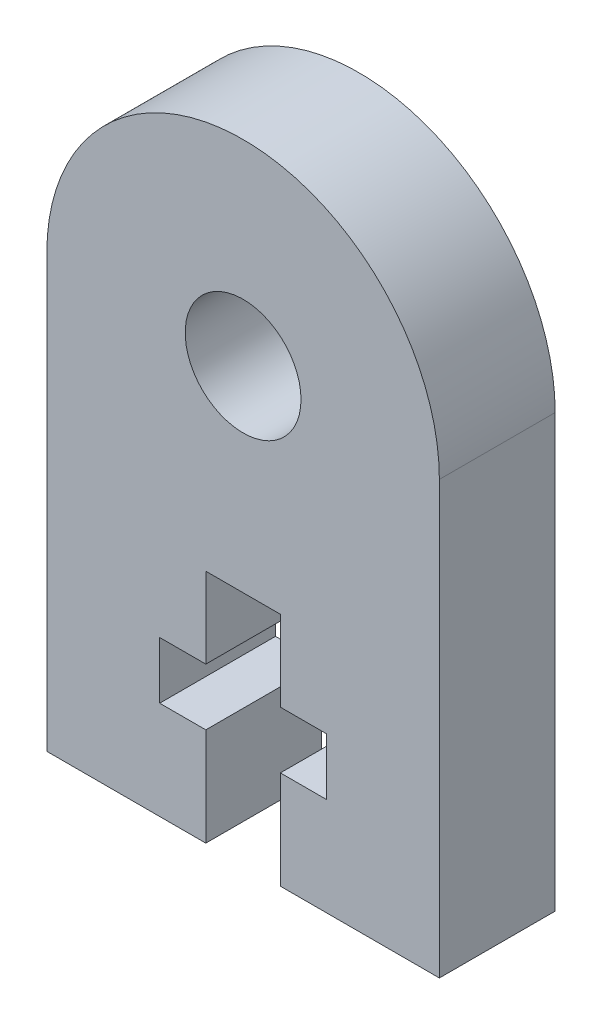
SolidWorks part; units mm, degrees
ref_plane "Front Plane" through (0, 0, 0) normal (0, 0, 1) x (1, 0, 0)
ref_plane "Top Plane" through (0, 0, 0) normal (0, 1, 0) x (1, 0, 0)
ref_plane "Right Plane" through (0, 0, 0) normal (1, 0, 0) x (0, 0, -1)
sketch "Sketch1" plane through (0, 0, 0) normal (0, 0, 1) x (1, 0, 0)
  line L0 (0, 0) -> (-2.086, 2.086) construction
  line L1 (0, 0) -> (0, 2.95) construction
  line L2 (-10, 0) -> (-10, -22)
  line L3 (-10, -22) -> (10, -22)
  line L4 (10, -22) -> (10, 0)
  line L5 (0, 0) -> (0, -22) construction
  circle A0 centre (0, 0) radius 2.95
  arc A1 (-10, 0) -> (10, 0) centre (0, 0) cw
  dimension "D1" = 5.9
  dimension "D4" = 45
  dimension "D5" = 22
  dimension "D6" = 20
extrude "Boss-Extrude1" add sketch "Sketch1" along normal blind 5.9
sketch "Sketch3" plane through (0, 0, 5.9) normal (0, 0, 1) x (1, 0, 0)
  line L0 (-10, -22) -> (10, -22) construction
  line L1 (-1.9, -22) -> (1.9, -22)
  line L2 (-1.9, -22) -> (-1.9, -17)
  line L3 (-1.9, -10) -> (1.9, -10)
  line L4 (1.9, -22) -> (1.9, -17)
  line L5 (0, -10) -> (0, 0) construction
  line L6 (1.9, -14.1) -> (4.25, -14.1)
  line L7 (-4.25, -14.1) -> (-1.9, -14.1)
  line L8 (-4.25, -14.1) -> (-4.25, -17)
  line L9 (-4.25, -17) -> (-1.9, -17)
  line L10 (4.25, -14.1) -> (4.25, -17)
  line L11 (-1.9, -14.1) -> (-1.9, -10)
  line L12 (1.9, -17) -> (4.25, -17)
  line L13 (1.9, -14.1) -> (1.9, -10)
  point P18 (-3.075, -17)
  dimension "D1" = 3.8
  dimension "D3" = 12
  dimension "D4" = 8.5
  dimension "D5" = 2.9
  dimension "D6" = 5
extrude "Cut-Extrude2" cut sketch "Sketch3" against normal through all
equation "\"smallPulleyTeeth\"= 15"
equation "\"largePulleyTeeth\"= 30"
equation "\"eighthThick\"= 2.9mm"
equation "\"sixteenthThick\" = 1.7mm"
equation "\"quarterThick\"=5.9mm"
equation "\"OD\" = 145mm"
equation "\"puckAngle\" = 60.5deg"
equation "\"puckDiam\" = 76.5mm"
equation "\"axlePress\" = 5.9mm"
equation "\"D1@Sketch1\"=\"axlePress\""
equation "\"D1@Boss-Extrude1\"=\"quarterThick\""
equation "\"press\" = 0.2mm"
equation "\"wheelClear\" = 0.3mm"
equation "\"10-32clear\" = 4.5mm"
equation "\"D1@Sketch3\"=\"8-32clear\"-\"press\""
equation "\"6-32clear\" = 3.3mm"
equation "\"8-32clear\" = 4.0mm"
equation "\"wheelHeight\" = 22mm"
equation "\"D5@Sketch1\"=\"wheelHeight\""
equation "\"wheelWell\" = 65mm"
